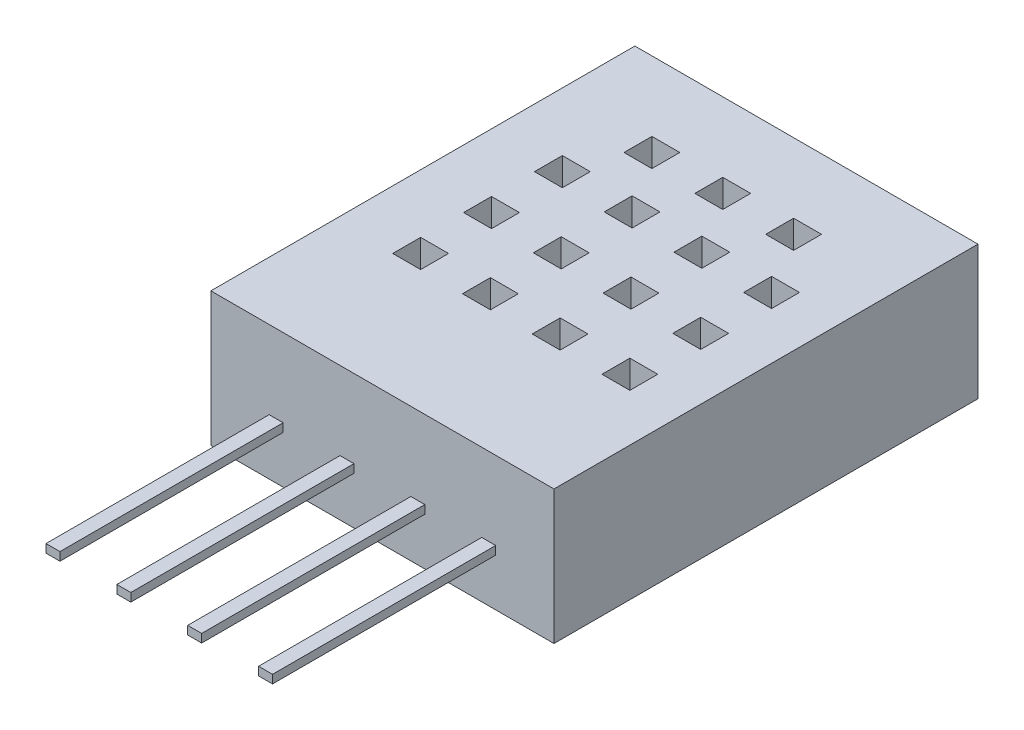
SolidWorks part; units mm, degrees
ref_plane "Front" through (0, 0, 0) normal (0, 0, 1) x (1, 0, 0)
ref_plane "Top" through (0, 0, 0) normal (0, 1, 0) x (1, 0, 0)
ref_plane "Right" through (0, 0, 0) normal (1, 0, 0) x (0, 0, -1)
sketch "Эскиз1" plane through (0, 0, 0) normal (0, 1, 0) x (1, 0, 0)
  line L1 (-6.15, -7.6) -> (6.15, -7.6)
  line L2 (-6.15, -7.6) -> (-6.15, 7.6)
  line L3 (-6.15, 7.6) -> (6.15, 7.6)
  line L4 (6.15, -7.6) -> (6.15, 7.6)
  line L5 (-6.15, -7.6) -> (6.15, 7.6) construction
  line L6 (-6.15, 7.6) -> (6.15, -7.6) construction
  point P0 (0, 0)
  dimension "D1" = 12.3
  dimension "D2" = 15.2
extrude "Бобышка-Вытянуть1" add sketch "Эскиз1" along normal blind 4.8
sketch "Эскиз2" plane through (0, 0, 7.6) normal (0, 0, 1) x (1, 0, 0)
  line L0 (-6.15, 0) -> (6.15, 0) construction
  line L1 (3.56, 1.7) -> (4.06, 1.7)
  line L2 (3.56, 1.7) -> (3.56, 2)
  line L3 (3.56, 2) -> (4.06, 2)
  line L4 (4.06, 1.7) -> (4.06, 2)
  line L5 (3.56, 1.7) -> (4.06, 2) construction
  line L6 (3.56, 2) -> (4.06, 1.7) construction
  point P0 (3.81, 1.85)
  dimension "D1" = 1.7
  dimension "D2" = 0.5
  dimension "D3" = 0.3
  dimension "D4" = 3.81
extrude "Бобышка-Вытянуть2" add sketch "Эскиз2" along normal blind 8 separate body
pattern_linear "Линейный массив1" count 4 spacing 2.54 along (-1, 0, 0) of bodies 102
sketch "Эскиз3" plane through (0, 4.8, 0) normal (0, 1, 0) x (1, 0, 0)
  line L0 (6.15, 7.6) -> (-6.15, 7.6) construction
  line L1 (-0.5, 5.1) -> (0.5, 5.1)
  line L2 (-0.5, 5.1) -> (-0.5, 4.1)
  line L3 (-0.5, 4.1) -> (0.5, 4.1)
  line L4 (0.5, 5.1) -> (0.5, 4.1)
  line L5 (-0.5, 5.1) -> (0.5, 4.1) construction
  line L6 (-0.5, 4.1) -> (0.5, 5.1) construction
  point P0 (0, 4.6)
  point P7 (0, 0)
  dimension "D1" = 2.5
  dimension "D2" = 1
extrude "Вырез-Вытянуть1" cut sketch "Эскиз3" against normal blind 2
pattern_linear "Линейный массив2" count 2 spacing 2.54 along (1, 0, 0) count 2 spacing 2.54 along (-1, 0, 0) of "Вырез-Вытянуть1"
sketch "Эскиз4" plane through (0, 4.8, 0) normal (0, 1, 0) x (1, 0, 0)
  line L0 (6.15, -7.6) -> (6.15, 7.6) construction
  line L1 (3.45, 2.9) -> (4.45, 2.9)
  line L2 (3.45, 2.9) -> (3.45, 1.9)
  line L3 (3.45, 1.9) -> (4.45, 1.9)
  line L4 (4.45, 2.9) -> (4.45, 1.9)
  line L5 (3.45, 2.9) -> (4.45, 1.9) construction
  line L6 (3.45, 1.9) -> (4.45, 2.9) construction
  line L7 (6.15, 7.6) -> (-6.15, 7.6) construction
  point P0 (3.95, 2.4)
  dimension "D1" = 1.7
  dimension "D2" = 1
  dimension "D3" = 4.7
extrude "Вырез-Вытянуть2" cut sketch "Эскиз4" against normal blind 2
pattern_linear "Линейный массив3" count 4 spacing 2.5 along (-1, 0, 0) count 3 spacing 2.54 along (0, 0, 1) of "Вырез-Вытянуть2"
